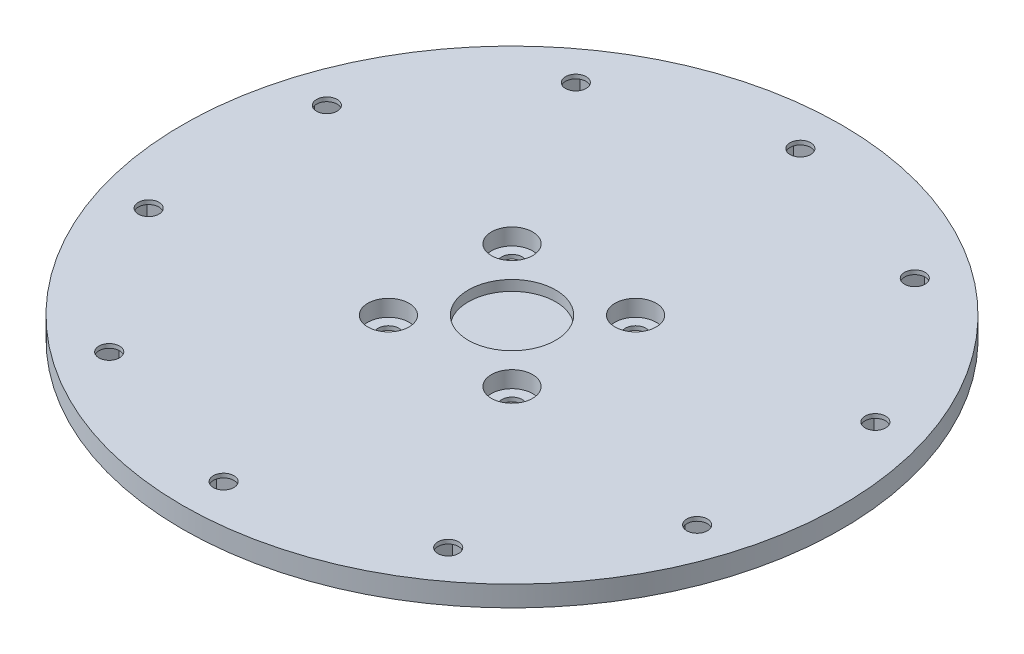
SolidWorks part; units mm, degrees
ref_plane "Front Plane" through (0, 0, 0) normal (0, 0, 1) x (1, 0, 0)
ref_plane "Top Plane" through (0, 0, 0) normal (0, 1, 0) x (1, 0, 0)
ref_plane "Right Plane" through (0, 0, 0) normal (1, 0, 0) x (0, 0, -1)
sketch "Sketch1" plane through (0, 0, 0) normal (0, 1, 0) x (1, 0, 0)
  line L1 (-15, -15) -> (15, -15) construction
  line L2 (-15, -15) -> (-15, 15) construction
  line L3 (-15, 15) -> (15, 15) construction
  line L4 (15, -15) -> (15, 15) construction
  line L5 (-15, -15) -> (15, 15) construction
  line L6 (-15, 15) -> (15, -15) construction
  circle A0 centre (0, 0) radius 80
  circle A1 centre (-15, 15) radius 2.5
  circle A2 centre (15, 15) radius 2.5
  circle A3 centre (15, -15) radius 2.5
  circle A4 centre (-15, -15) radius 2.5
  dimension "D1" = 160
  dimension "D4" = 5
  dimension "D2" = 30
  dimension "D3" = 30
extrude "Boss-Extrude1" add sketch "Sketch1" along normal blind 4
sketch "Sketch2" plane through (0, 4, 0) normal (0, 1, 0) x (1, 0, 0)
  line L0 (0, 0) -> (0, 70) construction
  line L1 (4, 70) -> (-4, 70) construction
  line L2 (4, 72.3094) -> (4, 67.6906)
  line L3 (-4, 72.3094) -> (-4, 67.6906)
  line L4 (-2, 66.5359) -> (2, 73.4641) construction
  line L5 (0, 65.3812) -> (-4, 67.6906)
  line L6 (4, 72.3094) -> (0, 74.6188)
  line L7 (-2, 73.4641) -> (2, 66.5359) construction
  line L8 (-4, 72.3094) -> (0, 74.6188)
  line L9 (0, 65.3812) -> (4, 67.6906)
  line L10 (45.7385, 56.1484) -> (43.0236, 52.4117)
  line L11 (38.4301, 52.8945) -> (43.0236, 52.4117)
  line L12 (38.4301, 52.8945) -> (36.5515, 57.114)
  line L13 (39.2663, 60.8507) -> (36.5515, 57.114)
  line L14 (39.2663, 60.8507) -> (43.8598, 60.3679)
  line L15 (45.7385, 56.1484) -> (43.8598, 60.3679)
  line L16 (37.4908, 55.0042) -> (44.7991, 58.2581) construction
  line L17 (41.5631, 60.6093) -> (40.7269, 52.6531) construction
  line L18 (0, 0) -> (41.145, 56.6312) construction
  line L19 (44.381, 54.28) -> (37.9089, 58.9823) construction
  line L20 (70.0064, 18.5406) -> (65.6137, 17.1133)
  line L21 (62.1812, 20.2039) -> (65.6137, 17.1133)
  line L22 (62.1812, 20.2039) -> (63.1415, 24.7218)
  line L23 (67.5343, 26.1491) -> (63.1415, 24.7218)
  line L24 (67.5343, 26.1491) -> (70.9667, 23.0585)
  line L25 (70.0064, 18.5406) -> (70.9667, 23.0585)
  line L26 (62.6614, 22.4628) -> (70.4865, 20.7995) construction
  line L27 (69.2505, 24.6038) -> (63.8974, 18.6586) construction
  line L28 (0, 0) -> (66.574, 21.6312) construction
  line L29 (67.81, 17.827) -> (65.3379, 25.4354) construction
  line L30 (67.5343, -26.1491) -> (63.1415, -24.7218)
  line L31 (62.1812, -20.2039) -> (63.1415, -24.7218)
  line L32 (62.1812, -20.2039) -> (65.6137, -17.1133)
  line L33 (70.0064, -18.5406) -> (65.6137, -17.1133)
  line L34 (70.0064, -18.5406) -> (70.9667, -23.0585)
  line L35 (67.5343, -26.1491) -> (70.9667, -23.0585)
  line L36 (63.8974, -18.6586) -> (69.2505, -24.6038) construction
  line L37 (70.4865, -20.7995) -> (62.6614, -22.4628) construction
  line L38 (0, 0) -> (66.574, -21.6312) construction
  line L39 (65.3379, -25.4354) -> (67.81, -17.827) construction
  line L40 (39.2663, -60.8507) -> (36.5515, -57.114)
  line L41 (38.4301, -52.8945) -> (36.5515, -57.114)
  line L42 (38.4301, -52.8945) -> (43.0236, -52.4117)
  line L43 (45.7385, -56.1484) -> (43.0236, -52.4117)
  line L44 (45.7385, -56.1484) -> (43.8598, -60.3679)
  line L45 (39.2663, -60.8507) -> (43.8598, -60.3679)
  line L46 (40.7269, -52.6531) -> (41.5631, -60.6093) construction
  line L47 (44.7991, -58.2581) -> (37.4908, -55.0042) construction
  line L48 (0, 0) -> (41.145, -56.6312) construction
  line L49 (37.9089, -58.9823) -> (44.381, -54.28) construction
  line L50 (-4, -72.3094) -> (-4, -67.6906)
  line L51 (0, -65.3812) -> (-4, -67.6906)
  line L52 (0, -65.3812) -> (4, -67.6906)
  line L53 (4, -72.3094) -> (4, -67.6906)
  line L54 (4, -72.3094) -> (0, -74.6188)
  line L55 (-4, -72.3094) -> (0, -74.6188)
  line L56 (2, -66.5359) -> (-2, -73.4641) construction
  line L57 (2, -73.4641) -> (-2, -66.5359) construction
  line L58 (0, 0) -> (0, -70) construction
  line L59 (-4, -70) -> (4, -70) construction
  line L60 (-45.7385, -56.1484) -> (-43.0236, -52.4117)
  line L61 (-38.4301, -52.8945) -> (-43.0236, -52.4117)
  line L62 (-38.4301, -52.8945) -> (-36.5515, -57.114)
  line L63 (-39.2663, -60.8507) -> (-36.5515, -57.114)
  line L64 (-39.2663, -60.8507) -> (-43.8598, -60.3679)
  line L65 (-45.7385, -56.1484) -> (-43.8598, -60.3679)
  line L66 (-37.4908, -55.0042) -> (-44.7991, -58.2581) construction
  line L67 (-41.5631, -60.6093) -> (-40.7269, -52.6531) construction
  line L68 (0, 0) -> (-41.145, -56.6312) construction
  line L69 (-44.381, -54.28) -> (-37.9089, -58.9823) construction
  line L70 (-70.0064, -18.5406) -> (-65.6137, -17.1133)
  line L71 (-62.1812, -20.2039) -> (-65.6137, -17.1133)
  line L72 (-62.1812, -20.2039) -> (-63.1415, -24.7218)
  line L73 (-67.5343, -26.1491) -> (-63.1415, -24.7218)
  line L74 (-67.5343, -26.1491) -> (-70.9667, -23.0585)
  line L75 (-70.0064, -18.5406) -> (-70.9667, -23.0585)
  line L76 (-62.6614, -22.4628) -> (-70.4865, -20.7995) construction
  line L77 (-69.2505, -24.6038) -> (-63.8974, -18.6586) construction
  line L78 (0, 0) -> (-66.574, -21.6312) construction
  line L79 (-67.81, -17.827) -> (-65.3379, -25.4354) construction
  line L80 (-67.5343, 26.1491) -> (-63.1415, 24.7218)
  line L81 (-62.1812, 20.2039) -> (-63.1415, 24.7218)
  line L82 (-62.1812, 20.2039) -> (-65.6137, 17.1133)
  line L83 (-70.0064, 18.5406) -> (-65.6137, 17.1133)
  line L84 (-70.0064, 18.5406) -> (-70.9667, 23.0585)
  line L85 (-67.5343, 26.1491) -> (-70.9667, 23.0585)
  line L86 (-63.8974, 18.6586) -> (-69.2505, 24.6038) construction
  line L87 (-70.4865, 20.7995) -> (-62.6614, 22.4628) construction
  line L88 (0, 0) -> (-66.574, 21.6312) construction
  line L89 (-65.3379, 25.4354) -> (-67.81, 17.827) construction
  line L90 (-39.2663, 60.8507) -> (-36.5515, 57.114)
  line L91 (-38.4301, 52.8945) -> (-36.5515, 57.114)
  line L92 (-38.4301, 52.8945) -> (-43.0236, 52.4117)
  line L93 (-45.7385, 56.1484) -> (-43.0236, 52.4117)
  line L94 (-45.7385, 56.1484) -> (-43.8598, 60.3679)
  line L95 (-39.2663, 60.8507) -> (-43.8598, 60.3679)
  line L96 (-40.7269, 52.6531) -> (-41.5631, 60.6093) construction
  line L97 (-44.7991, 58.2581) -> (-37.4908, 55.0042) construction
  line L98 (0, 0) -> (-41.145, 56.6312) construction
  line L99 (-37.9089, 58.9823) -> (-44.381, 54.28) construction
  point P6 (0, 70)
  point P9 (4, 70)
  point P12 (-4, 70)
  point P27 (0, 70)
  point P138 (0, 0)
  dimension "D1" = 8
  dimension "D3" = 70
  dimension "D2" = 3
extrude "Cut-Extrude1" cut sketch "Sketch2" against normal through all
sketch "Sketch3" plane through (0, 4, 0) normal (0, 1, 0) x (1, 0, 0)
  circle A0 centre (-15, -15) radius 5
  circle A1 centre (15, -15) radius 5
  circle A2 centre (15, 15) radius 5
  circle A3 centre (-15, 15) radius 5
  dimension "D1" = 10
extrude "Cut-Extrude2" cut sketch "Sketch3" against normal blind 3
sketch "Sketch4" plane through (0, 4, 0) normal (0, 1, 0) x (1, 0, 0)
  line L0 (0, 74.6188) -> (0, 65.3812) construction
  line L1 (43.8598, 60.3679) -> (38.4301, 52.8945) construction
  line L2 (70.9667, 23.0585) -> (62.1812, 20.2039) construction
  line L3 (70.9667, -23.0585) -> (62.1812, -20.2039) construction
  line L4 (43.8598, -60.3679) -> (38.4301, -52.8945) construction
  line L5 (0, -74.6188) -> (0, -65.3812) construction
  line L6 (-43.8598, -60.3679) -> (-38.4301, -52.8945) construction
  line L7 (-70.9667, -23.0585) -> (-62.1812, -20.2039) construction
  line L8 (-70.9667, 23.0585) -> (-62.1812, 20.2039) construction
  line L9 (-43.8598, 60.3679) -> (-38.4301, 52.8945) construction
  circle A0 centre (41.145, 56.6312) radius 2.5
  circle A1 centre (0, 70) radius 2.5
  circle A2 centre (0, 0) radius 80
  circle A3 centre (0, 0) radius 80
  circle A11 centre (66.574, 21.6312) radius 2.5
  circle A12 centre (66.574, -21.6312) radius 2.5
  circle A13 centre (-15, 15) radius 5
  circle A14 centre (-15, 15) radius 5
  circle A15 centre (41.145, -56.6312) radius 2.5
  circle A16 centre (15, 15) radius 5
  circle A17 centre (15, 15) radius 5
  circle A18 centre (0, -70) radius 2.5
  circle A19 centre (-15, -15) radius 5
  circle A20 centre (-15, -15) radius 5
  circle A21 centre (-41.145, -56.6312) radius 2.5
  circle A22 centre (15, -15) radius 5
  circle A23 centre (15, -15) radius 5
  circle A24 centre (-66.574, -21.6312) radius 2.5
  circle A25 centre (-66.574, 21.6312) radius 2.5
  circle A26 centre (-41.145, 56.6312) radius 2.5
  point P39 (0, 0)
  point P61 (0, 0)
  dimension "D2" = 5
  dimension "D1" = 0
  dimension "D4" = 0
  dimension "D5" = 0
  dimension "D6" = 0
  dimension "D7" = 0
extrude "Boss-Extrude2" add sketch "Sketch4" along normal blind 1
sketch "Sketch5" plane through (0, 5, 0) normal (0, 1, 0) x (1, 0, 0)
  circle A0 centre (0, 0) radius 10.6
  dimension "D1" = 21.2
extrude "Cut-Extrude3" cut sketch "Sketch5" against normal blind 2.5
